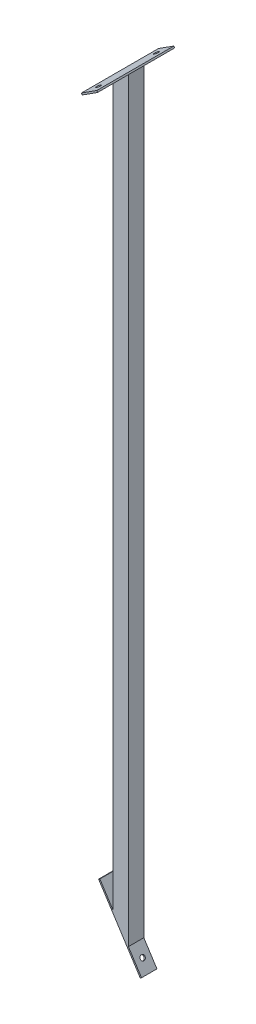
SolidWorks part; units mm, degrees
ref_plane "Front Plane" through (0, 0, 0) normal (0, 0, 1) x (1, 0, 0)
ref_plane "Top Plane" through (0, 0, 0) normal (0, 1, 0) x (1, 0, 0)
ref_plane "Right Plane" through (0, 0, 0) normal (1, 0, 0) x (0, 0, -1)
sketch "Sketch1" plane through (0, 0, 0) normal (0, 0, 1) x (1, 0, 0)
  line L0 (0, 0) -> (0, 988.9)
  dimension "D1" = 988.9
other "Al tube square AL TUBE 0.75 SQR X 0.065 WALL(1)"
ref_plane "Plane1" through (0, 0, 0) normal (0, 1, 0) x (-1, 0, 0)
sketch "Sketch15" plane through (0, 0, 0) normal (0, 1, 0) x (-1, 0, 0)
  line L0 (-8, -8) -> (-8, 8)
  line L1 (8, 8) -> (-8, 8)
  line L2 (8, 8) -> (8, -8)
  line L3 (-8, -8) -> (8, -8)
  line L4 (-10, -10) -> (10, -10)
  line L5 (-10, -10) -> (-10, 10)
  line L6 (10, 10) -> (-10, 10)
  line L7 (10, 10) -> (10, -10)
  line L8 (0, -8) -> (0, -10) construction
  line L9 (0, -8) -> (0, 8) construction
  line L10 (0, 8) -> (0, 10) construction
  line L11 (10, 0) -> (8, 0) construction
  line L12 (8, 0) -> (-8, 0) construction
  line L13 (-8, 0) -> (-10, 0) construction
  point P14 (0, 0)
  point P17 (0, 0)
  dimension "Thickness" = 2
  dimension "V_leg" = 20
  dimension "H_leg" = 20
sketch "Sketch16" plane through (0, 0, 10) normal (0, 0, 1) x (1, 0, 0)
  line L0 (0, 988.9) -> (0, 0) construction
  circle A0 centre (0, 10) radius 5
  dimension "D1" = 10
  dimension "D2" = 10
extrude "Cut-Extrude1" cut sketch "Sketch16" against normal through all
sketch "Sketch17" plane through (0, 0, 10) normal (0, 0, 1) x (1, 0, 0)
  line L0 (10, 988.9) -> (-10, 976.0417)
  line L7 (-10, 988.9) -> (-10, 0) construction
  line L9 (10, 988.9) -> (-10, 988.9)
  line L10 (-10, 988.9) -> (-10, 976.0417)
  dimension "D1" = 32.738
extrude "Cut-Extrude3" cut sketch "Sketch17" against normal through all
sketch "Sketch18" plane through (0, 0, -10) normal (0, 0, -1) x (-1, 0, 0)
  line L0 (-10, 988.9) -> (435.8128, 702.2802) construction
  line L1 (10, 976.0417) -> (-10, 988.9) construction
  line L2 (435.8128, 702.2802) -> (-104.9792, -138.8761) construction
  line L3 (-15.4813, 0.3303) -> (41.3623, 88.7457)
  line L4 (41.3623, 88.7457) -> (41.3623, -42.243)
  line L5 (41.3623, -42.243) -> (-15.4813, -42.243)
  line L6 (-15.4813, -42.243) -> (-15.4813, 0.3303)
  dimension "D1" = 530
  dimension "D2" = 1000
extrude "Cut-Extrude4" cut sketch "Sketch18" against normal through all both and the other way through all
sketch "Sketch19" plane through (11.104, 7.1389, 0) normal (-0.8412, -0.5408, 0) x (0, 0, 1)
  line L0 (0, 39.0242) -> (0, 2.0414) construction
  line L1 (-10, 39.0242) -> (10, 39.0242) construction
  line L2 (10, 2.0414) -> (-10, 2.0414) construction
  line L4 (-10, -29.4672) -> (10, -29.4672)
  line L5 (-10, -29.4672) -> (-10, 70.5328)
  line L6 (-10, 70.5328) -> (10, 70.5328)
  line L7 (10, -29.4672) -> (10, 70.5328)
  line L8 (-10, -29.4672) -> (10, 70.5328) construction
  line L9 (-10, 70.5328) -> (10, -29.4672) construction
  point P6 (0, 20.5328)
  dimension "D1" = 100
extrude "Boss-Extrude1" add sketch "Sketch19" along normal blind 2
sketch "Sketch20" plane through (-446.9168, 695.1413, 0) normal (-0.5408, 0.8412, 0) x (0.8412, 0.5408, 0)
  line L0 (519.424, 0) -> (543.2008, 0) construction
  line L1 (519.424, 10) -> (519.424, -10) construction
  line L2 (543.2008, -10) -> (543.2008, 10) construction
  line L4 (481.3124, -10) -> (581.3124, -10) construction
  line L5 (481.3124, -10) -> (481.3124, 10) construction
  line L6 (481.3124, 10) -> (581.3124, 10) construction
  line L7 (581.3124, -10) -> (581.3124, 10) construction
  line L8 (481.3124, -10) -> (581.3124, 10) construction
  line L9 (481.3124, 10) -> (581.3124, -10) construction
  line L10 (519.424, -50) -> (543.2008, -50)
  line L11 (519.424, -50) -> (519.424, 50)
  line L12 (519.424, 50) -> (543.2008, 50)
  line L13 (543.2008, -50) -> (543.2008, 50)
  line L14 (519.424, -50) -> (543.2008, 50) construction
  line L15 (519.424, 50) -> (543.2008, -50) construction
  point P6 (531.3124, 0)
  point P11 (531.3124, 0)
  dimension "D1" = 100
extrude "Boss-Extrude2" add sketch "Sketch20" along normal blind 2
sketch "Sketch22" plane through (-447.9984, 696.8236, 0) normal (-0.5408, 0.8412, 0) x (0.8412, 0.5408, 0)
  line L0 (531.3124, 50) -> (531.3124, -50) construction
  line L1 (543.2008, 50) -> (519.424, 50) construction
  line L2 (519.424, -50) -> (543.2008, -50) construction
  line L3 (531.3124, 0) -> (585.1887, 0) construction
  circle A0 centre (531.3124, 37.5) radius 3.125
  circle A1 centre (531.3124, -37.5) radius 3.125
  dimension "D1" = 6.25
  dimension "D2" = 75
extrude "Cut-Extrude5" cut sketch "Sketch22" against normal blind 2
sketch "Sketch23" plane through (11.104, 7.1389, 0) normal (0.8412, 0.5408, 0) x (0, 0, -1)
  line L0 (0, -29.4672) -> (0, 2.0414) construction
  line L1 (10, -29.4672) -> (-10, -29.4672) construction
  line L2 (-10, 2.0414) -> (10, 2.0414) construction
  circle A0 centre (0, -13.7129) radius 3.125
  dimension "D1" = 6.25
extrude "Cut-Extrude6" cut sketch "Sketch23" against normal blind 2
